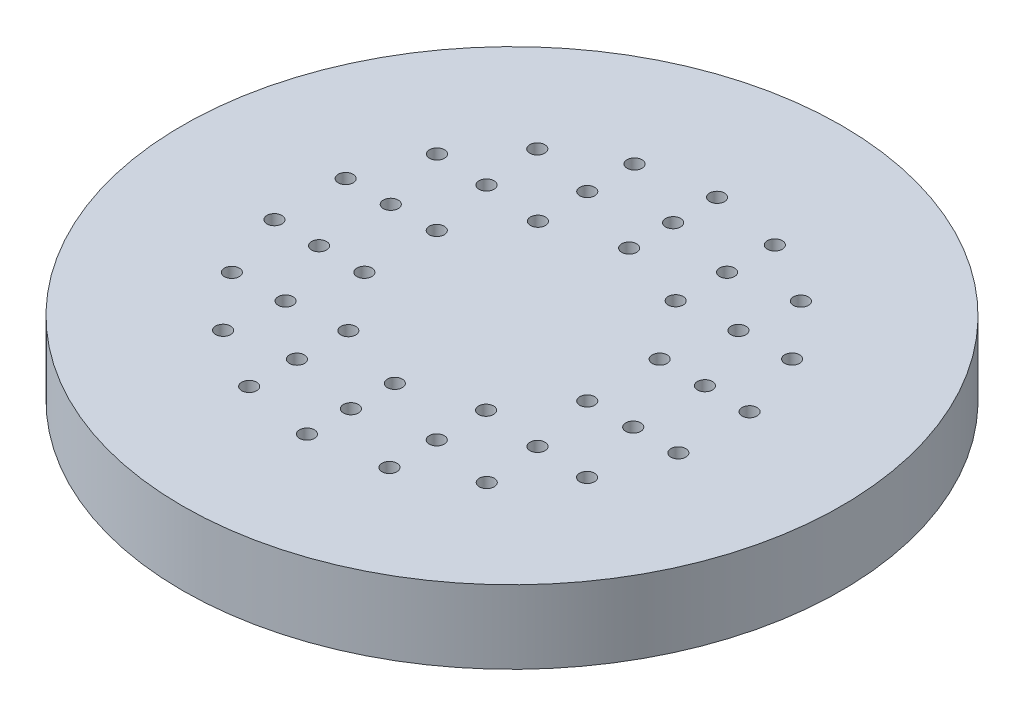
SolidWorks part; units mm, degrees
material "AISI 304"
ref_plane "Front Plane" through (0, 0, 0) normal (0, 0, 1) x (1, 0, 0)
ref_plane "Top Plane" through (0, 0, 0) normal (0, 1, 0) x (1, 0, 0)
ref_plane "Right Plane" through (0, 0, 0) normal (1, 0, 0) x (0, 0, -1)
sketch "Main Shape Profile" plane through (0, 0, 0) normal (0, 0, 1) x (1, 0, 0)
  line L0 (0, 0) -> (0, -36934.052) construction
  line L1 (0, 0) -> (28.575, 0)
  line L2 (28.575, 0) -> (28.575, 6.35)
  line L3 (28.575, 6.35) -> (0, 6.35)
  line L4 (0, 6.35) -> (0, 0)
  dimension "LOX OD" = 57.15
  dimension "LOX Thickness" = 6.35
revolve "Main Shape" add sketch "Main Shape Profile" angle 360 about L0
sketch "Dowel Holes Profile" plane through (0, 0, 0) normal (0, -1, 0) x (1, 0, 0)
  line L0 (0, 25.4) -> (0, -25.4) construction
  circle A0 centre (0, 25.4) radius 1.27
  circle A1 centre (0, -25.4) radius 1.27
  point P4 (0, 0)
  dimension "Dowel Holes Diameter" = 2.54
  dimension "Dowel Placement Inner Diameter" = 50.8
extrude "Dowel Holes" cut sketch "Dowel Holes Profile" against normal blind 2.54
sketch "Injector Holes Profile" plane through (0, 6.35, 0) normal (0, 1, 0) x (1, 0, 0)
  line L0 (0, 0) -> (0, 10.16) construction
  line L1 (0, 10.16) -> (0, 13.97) construction
  line L2 (0, 13.97) -> (0, 17.78) construction
  circle A2 centre (0, 10.16) radius 0.6477
  circle A3 centre (0, 13.97) radius 0.6477
  circle A4 centre (0, 17.78) radius 0.6477
  circle A5 centre (0, 0) radius 10.16 construction
  circle A7 centre (0, 0) radius 17.78 construction
  circle A8 centre (5.9719, 8.2196) radius 0.6477
  circle A9 centre (9.6627, 3.1396) radius 0.6477
  circle A10 centre (9.6627, -3.1396) radius 0.6477
  circle A11 centre (5.9719, -8.2196) radius 0.6477
  circle A12 centre (0, -10.16) radius 0.6477
  circle A13 centre (-5.9719, -8.2196) radius 0.6477
  circle A14 centre (-9.6627, -3.1396) radius 0.6477
  circle A15 centre (-9.6627, 3.1396) radius 0.6477
  circle A16 centre (-5.9719, 8.2196) radius 0.6477
  circle A19 centre (6.0614, 12.5865) radius 0.6477
  circle A20 centre (10.9222, 8.7102) radius 0.6477
  circle A21 centre (13.6197, 3.1086) radius 0.6477
  circle A22 centre (13.6197, -3.1086) radius 0.6477
  circle A23 centre (10.9222, -8.7102) radius 0.6477
  circle A24 centre (6.0614, -12.5865) radius 0.6477
  circle A25 centre (0, -13.97) radius 0.6477
  circle A26 centre (-6.0614, -12.5865) radius 0.6477
  circle A27 centre (-10.9222, -8.7102) radius 0.6477
  circle A28 centre (-13.6197, -3.1086) radius 0.6477
  circle A29 centre (-13.6197, 3.1086) radius 0.6477
  circle A30 centre (-10.9222, 8.7102) radius 0.6477
  circle A31 centre (-6.0614, 12.5865) radius 0.6477
  circle A32 centre (6.0811, 16.7077) radius 0.6477
  circle A33 centre (11.4288, 13.6203) radius 0.6477
  circle A34 centre (15.3979, 8.89) radius 0.6477
  circle A35 centre (17.5099, 3.0875) radius 0.6477
  circle A36 centre (17.5099, -3.0875) radius 0.6477
  circle A37 centre (15.3979, -8.89) radius 0.6477
  circle A38 centre (11.4288, -13.6203) radius 0.6477
  circle A39 centre (6.0811, -16.7077) radius 0.6477
  circle A40 centre (0, -17.78) radius 0.6477
  circle A41 centre (-6.0811, -16.7077) radius 0.6477
  circle A42 centre (-11.4288, -13.6203) radius 0.6477
  circle A43 centre (-15.3979, -8.89) radius 0.6477
  circle A44 centre (-17.5099, -3.0875) radius 0.6477
  circle A45 centre (-17.5099, 3.0875) radius 0.6477
  circle A46 centre (-15.3979, 8.89) radius 0.6477
  circle A47 centre (-11.4288, 13.6203) radius 0.6477
  circle A48 centre (-6.0811, 16.7077) radius 0.6477
  point P34 (0, 0)
  point P62 (0, 0)
  point P97 (0, 0)
  dimension "Injector Hole Inner Diameter" = 20.32
  dimension "Injector Hole Outer Diameter" = 35.56
  dimension "LOX Injector Hole Diameter" = 1.2954
  dimension "Inner Ring Num" = 10
  dimension "Middle Ring Num" = 14
  dimension "Outer Ring Num" = 18
hole_wizard "3/8-16 Tapped Hole1" positions "Sketch4" profile "Sketch5" tap size "3/8-16" standard "ANSI Inch" end condition through all
sketch "Sketch4" plane through (0, 6.35, 0) normal (0, 1, 0) x (1, 0, 0)
  point P3 (-5.9719, -8.2196)
  point P6 (0, -13.97)
  point P9 (0, -17.78)
  point P17 (-9.6627, -3.1396)
  point P18 (-9.6627, 3.1396)
  point P19 (-5.9719, 8.2196)
  point P20 (0, 10.16)
  point P21 (5.9719, 8.2196)
  point P22 (9.6627, 3.1396)
  point P23 (9.6627, -3.1396)
  point P24 (5.9719, -8.2196)
  point P25 (0, -10.16)
  point P35 (-6.0614, -12.5865)
  point P36 (-10.9222, -8.7102)
  point P37 (-13.6197, -3.1086)
  point P38 (-13.6197, 3.1086)
  point P39 (-10.9222, 8.7102)
  point P40 (-6.0614, 12.5865)
  point P41 (0, 13.97)
  point P42 (6.0614, 12.5865)
  point P43 (10.9222, 8.7102)
  point P44 (13.6197, 3.1086)
  point P45 (13.6197, -3.1086)
  point P46 (10.9222, -8.7102)
  point P47 (6.0614, -12.5865)
  point P55 (-6.0811, -16.7077)
  point P56 (-11.4288, -13.6203)
  point P57 (-15.3979, -8.89)
  point P58 (-17.5099, -3.0875)
  point P59 (-17.5099, 3.0875)
  point P60 (-15.3979, 8.89)
  point P61 (-11.4288, 13.6203)
  point P62 (-6.0811, 16.7077)
  point P63 (0, 17.78)
  point P64 (6.0811, 16.7077)
  point P65 (11.4288, 13.6203)
  point P66 (15.3979, 8.89)
  point P67 (17.5099, 3.0875)
  point P68 (17.5099, -3.0875)
  point P69 (15.3979, -8.89)
  point P70 (11.4288, -13.6203)
  point P71 (6.0811, -16.7077)
  dimension "D1" = 10
  dimension "D2" = 14
  dimension "D3" = 18
sketch "Sketch5" plane through (-5.9719, 6.35, 8.2196) normal (1, 0, 0) x (0, 0, 1)
  line L0 (0, 0) -> (0, 6.35)
  line L1 (0, 6.35) -> (0.6477, 6.35)
  line L2 (0.6477, 6.35) -> (0.6477, 0)
  line L5 (0.6477, 0) -> (0, 0)
  line L11 (0, -6.35) -> (0, 107.95) construction
  dimension "Thru Tap Drill Dia." = 1.2954
  dimension "Thru Tap Drill Depth" = 6.35
equation "\"D1@Sketch4\"= \"Inner Ring Num@Injector Holes Profile\""
equation "\"D2@Sketch4\"= \"Middle Ring Num@Injector Holes Profile\""
equation "\"D3@Sketch4\"= \"Outer Ring Num@Injector Holes Profile\""
equation "\"Thru Tap Drill Dia.@Sketch5\"= \"LOX Injector Hole Diameter@Injector Holes Profile\""
